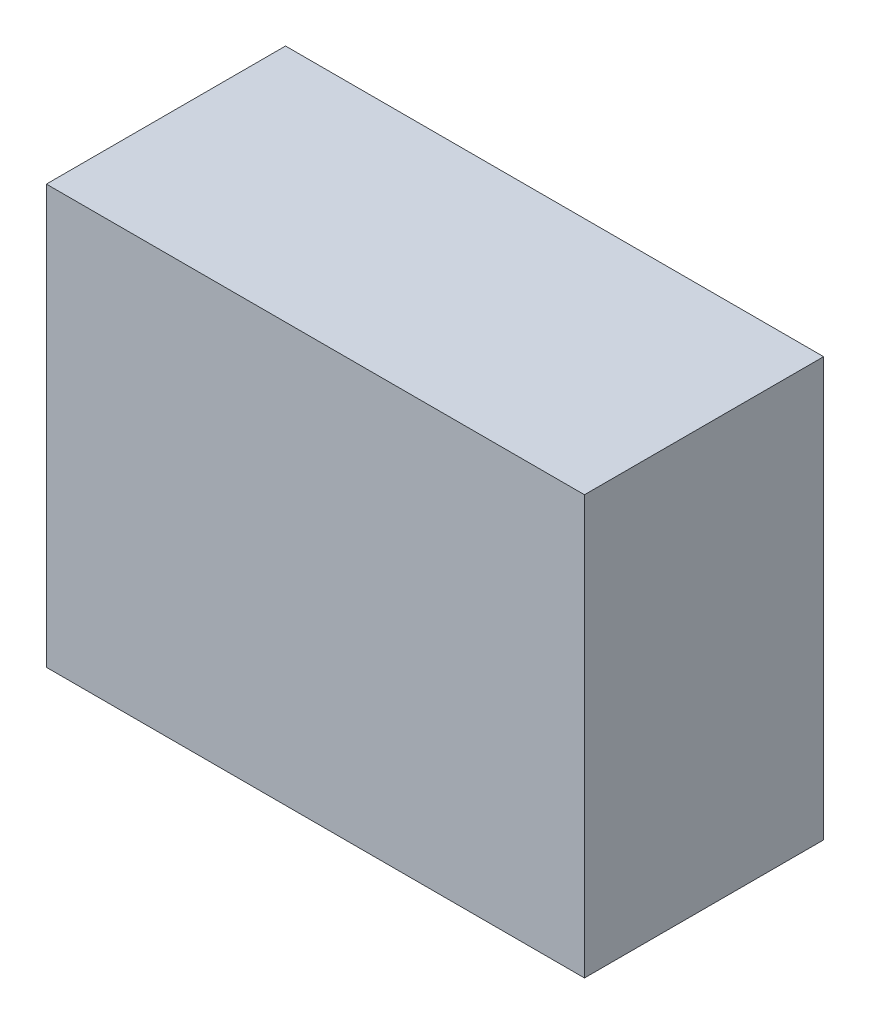
SolidWorks part; units mm, degrees
ref_plane "Front Plane" through (0, 0, 0) normal (0, 0, 1) x (1, 0, 0)
ref_plane "Top Plane" through (0, 0, 0) normal (0, 1, 0) x (1, 0, 0)
ref_plane "Right Plane" through (0, 0, 0) normal (1, 0, 0) x (0, 0, -1)
sketch "Sketch1" plane through (0, 0, 0) normal (0, 0, 1) x (1, 0, 0)
  line L1 (228.6, 177.8) -> (-228.6, 177.8)
  line L2 (228.6, 177.8) -> (228.6, -177.8)
  line L3 (228.6, -177.8) -> (-228.6, -177.8)
  line L4 (-228.6, 177.8) -> (-228.6, -177.8)
  line L5 (228.6, 177.8) -> (-228.6, -177.8) construction
  line L6 (228.6, -177.8) -> (-228.6, 177.8) construction
  point P0 (0, 0)
  dimension "D1" = 457.2
  dimension "D2" = 355.6
extrude "Boss-Extrude1" add sketch "Sketch1" along normal blind 203.2
